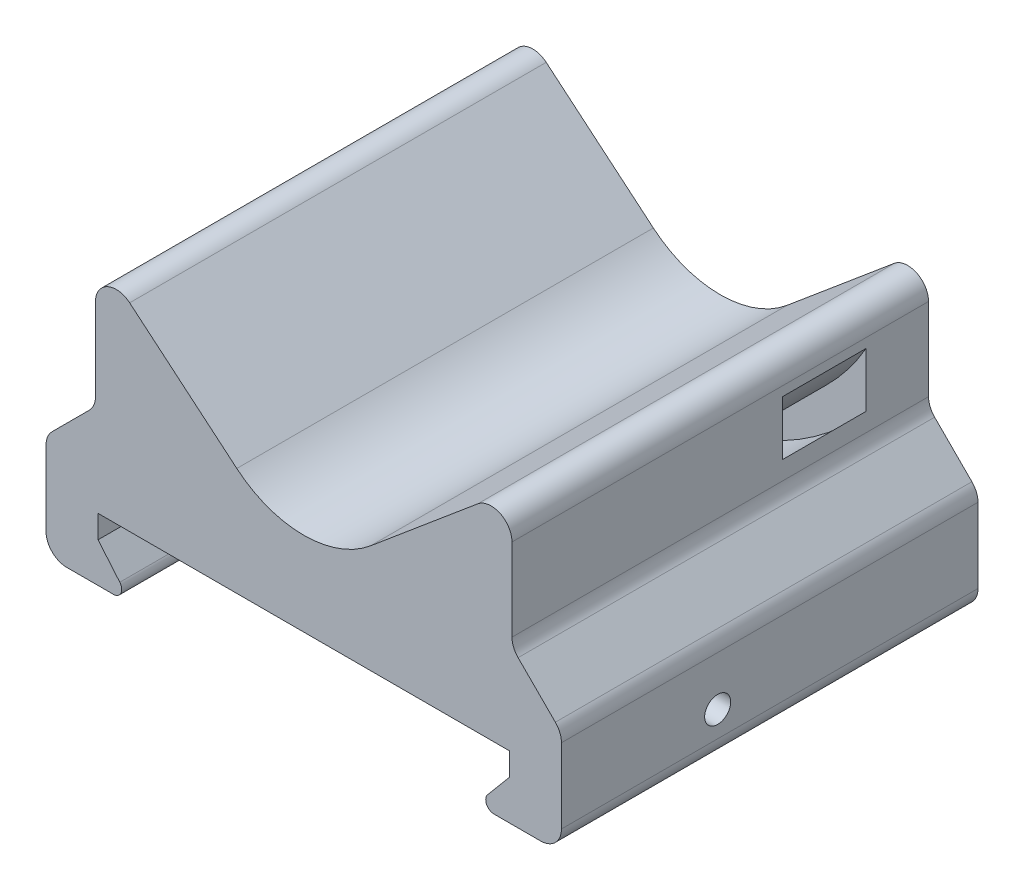
SolidWorks part; units mm, degrees
ref_plane "Front Plane" through (0, 0, 0) normal (0, 0, 1) x (1, 0, 0)
ref_plane "Top Plane" through (0, 0, 0) normal (0, 1, 0) x (1, 0, 0)
ref_plane "Right Plane" through (0, 0, 0) normal (1, 0, 0) x (0, 0, -1)
sketch "Sketch1" plane through (0, 0, 0) normal (0, 0, 1) x (1, 0, 0)
  line L0 (0, 15.6125) -> (0, -8.5333) construction
  line L1 (6.4279, 10.3936) -> (16.7144, 19.0251)
  line L2 (20, 17.493) -> (20, 9.5784)
  line L3 (20.5858, 8.1642) -> (24.1642, 4.5858)
  line L4 (24.75, 3.1716) -> (24.75, -4)
  line L5 (22.75, -6) -> (18.277, -6)
  line L7 (19.75, 0) -> (-19.75, 0)
  line L9 (-22.75, -6) -> (-18.277, -6)
  line L10 (-24.75, 3.1716) -> (-24.75, -4)
  line L11 (-20.5858, 8.1642) -> (-24.1642, 4.5858)
  line L12 (-20, 17.493) -> (-20, 9.5784)
  line L13 (-6.4279, 10.3936) -> (-16.7144, 19.0251)
  line L14 (-19.05, -0.1) -> (19.05, -0.1) construction
  line L15 (19.05, -0.1) -> (19.05, -2.1) construction
  line L16 (19.05, -2.1) -> (13.05, -8.1) construction
  line L17 (13.05, -8.1) -> (-13.05, -8.1) construction
  line L18 (-13.05, -8.1) -> (-19.05, -2.1) construction
  line L19 (-19.05, -0.1) -> (-19.05, -2.1) construction
  line L20 (17.6642, -4.6858) -> (19.75, -2.2)
  line L21 (19.75, -2.2) -> (19.75, 0)
  line L22 (-19.75, -2.2) -> (-19.75, 0)
  line L23 (-17.6642, -4.6858) -> (-19.75, -2.2)
  arc A0 (-6.4279, 10.3936) -> (6.4279, 10.3936) centre (0, 18.0541) ccw
  arc A1 (20, 9.5784) -> (20.5858, 8.1642) centre (22, 9.5784) ccw
  arc A2 (24.1642, 4.5858) -> (24.75, 3.1716) centre (22.75, 3.1716) cw
  arc A3 (24.75, -4) -> (22.75, -6) centre (22.75, -4) cw
  arc A4 (-22.75, -6) -> (-24.75, -4) centre (-22.75, -4) cw
  arc A5 (-24.75, 3.1716) -> (-24.1642, 4.5858) centre (-22.75, 3.1716) cw
  arc A6 (-20.5858, 8.1642) -> (-20, 9.5784) centre (-22, 9.5784) ccw
  arc A7 (16.7144, 19.0251) -> (20, 17.493) centre (18, 17.493) cw
  arc A8 (-20, 17.493) -> (-16.7144, 19.0251) centre (-18, 17.493) cw
  arc A9 (18.277, -6) -> (17.6642, -4.6858) centre (18.277, -5.2) cw
  arc A10 (-17.6642, -4.6858) -> (-18.277, -6) centre (-18.277, -5.2) cw
  point P11 (0, 0)
  point P19 (0, 5)
  point P22 (20, 8.75)
  point P25 (24.75, 4)
  point P28 (24.75, -6)
  point P31 (-24.75, -6)
  point P34 (-24.75, 4)
  point P37 (-20, 8.75)
  point P40 (20, 21.782)
  point P43 (-20, 21.782)
  point P51 (0, -8.1)
  point P52 (0, -0.1)
  point P56 (16.5614, -6)
  point P59 (-16.5614, -6)
  dimension "D10" = 10
  dimension "D11" = 2
  dimension "D18" = 0.8
  dimension "D1" = 19.75
  dimension "D2" = 5
  dimension "D3" = 20
  dimension "D4" = 135
  dimension "D5" = 50
  dimension "D6" = 6
  dimension "D7" = 4
  dimension "D8" = 50
  dimension "D9" = 5
  dimension "D12" = 38.1
  dimension "D13" = 135
  dimension "D14" = 8
  dimension "D15" = 2
  dimension "D16" = 0.2
  dimension "D17" = 2.2
extrude "Boss-Extrude1" add sketch "Sketch1" along normal blind 40
sketch "Sketch2" plane through (0, 0, 0) normal (1, 0, 0) x (0, 0, -1)
  line L0 (-40, 0) -> (0, 0) construction
  line L1 (-6, 5) -> (-14, 5)
  line L2 (-6, 5) -> (-6, 2)
  line L3 (-6, 2) -> (-14, 2)
  line L4 (-14, 5) -> (-14, 2)
  line L5 (0, 4.5858) -> (0, 8.1642) construction
  line L6 (-46, 5) -> (-54, 5)
  line L7 (-46, 5) -> (-46, 2)
  line L8 (-46, 2) -> (-54, 2)
  line L9 (-54, 5) -> (-54, 2)
  line L10 (-86, 5) -> (-94, 5)
  line L11 (-86, 5) -> (-86, 2)
  line L12 (-86, 2) -> (-94, 2)
  line L13 (-94, 5) -> (-94, 2)
  line L14 (-29.3538, 28.0541) -> (55.5998, 28.0541) construction
  line L15 (-40, 8.0541) -> (0, 8.0541) construction
  dimension "D1" = 8
  dimension "D2" = 3
  dimension "D3" = 2
  dimension "D4" = 6
  dimension "D6" = 20
  dimension "D5" = 3
revolve "Cut-Revolve1" cut sketch "Sketch2" angle 360 about L14
hole_wizard "M3x0.5 Tapped Hole1" positions "Sketch3" profile "Sketch4" tap size "M3x0.5" standard "ANSI Metric" end condition through all
sketch "Sketch3" plane through (-24.75, 0, 0) normal (-1, 0, 0) x (0, 0, 1)
  line L0 (75, -1.5555) -> (25, -1.5555) construction
  point P0 (25, -1.5555)
  point P2 (75, -1.5555)
  point P10 (50, -1.5555)
  dimension "D1" = 50
  dimension "D2" = 50
sketch "Sketch4" plane through (-24.75, -1.5555, 25) normal (0, 1, 0) x (0, 0, 1)
  line L0 (0, 0) -> (0, 49.5)
  line L1 (0, 49.5) -> (1.25, 49.5)
  line L2 (1.25, 49.5) -> (1.25, 0.275)
  line L3 (1.25, 0.275) -> (1.525, 0)
  line L5 (1.525, 0) -> (0, 0)
  line L6 (-1.25, 0.275) -> (-1.525, 0) construction
  line L11 (0, -6.35) -> (0, 107.95) construction
  dimension "Thru Tap Drill Dia." = 2.5
  dimension "Thru Tap Drill Depth" = 49.5
  dimension "Near C'Sink Dia." = 3.05
  dimension "Near C'Sink Angle" = 90
cosmetic thread "Hole Thread2" parameters "D2"=3
